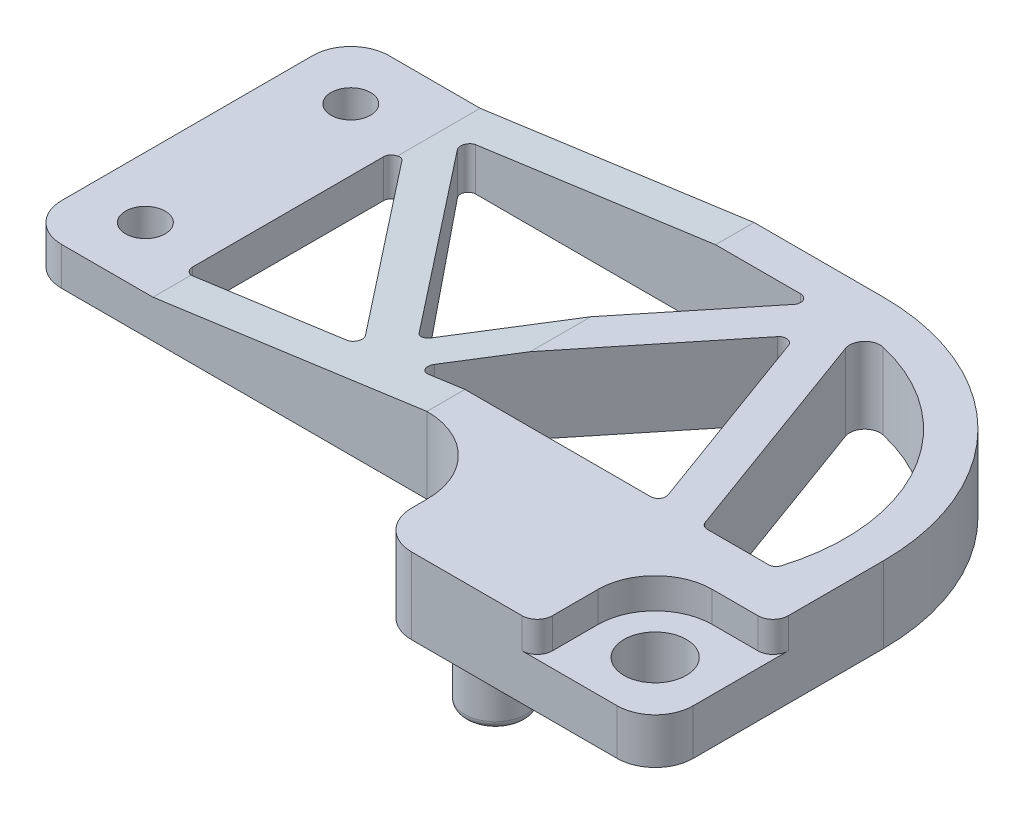
SolidWorks part; units mm, degrees
ref_plane "Front Plane" through (0, 0, 0) normal (0, 0, 1) x (1, 0, 0)
ref_plane "Top Plane" through (0, 0, 0) normal (0, 1, 0) x (1, 0, 0)
ref_plane "Right Plane" through (0, 0, 0) normal (1, 0, 0) x (0, 0, -1)
sketch "Sketch1" plane through (0, 0, 0) normal (0, 1, 0) x (1, 0, 0)
  line L0 (-15.9009, 67.2516) -> (-15.9009, 34.3134) construction
  line L1 (11.2739, 72.3134) -> (4.7921, 72.3134)
  line L2 (41.2739, 42.3134) -> (41.2739, 17.3134)
  line L3 (36.2739, 12.3134) -> (9.2739, 12.3134)
  line L4 (4.2739, 19.3134) -> (4.2739, 17.3134)
  line L5 (4.7921, 72.3134) -> (-53.7261, 72.3134)
  line L7 (-5.7261, 29.3134) -> (-53.7261, 29.3134)
  line L8 (-58.7261, 67.3134) -> (-58.7261, 34.3134)
  line L9 (34.1714, 34.3134) -> (26.1348, 34.3134)
  line L10 (-42.5577, 35.3134) -> (-42.5577, 60.4524)
  line L11 (-37.2458, 67.2516) -> (5.4439, 67.2516)
  line L12 (-42.5577, 67.2516) -> (-15.9009, 34.3134) construction
  line L13 (10.7558, 67.2516) -> (22.7739, 34.3134) construction
  line L14 (-15.9009, 34.3134) -> (10.7558, 67.2516) construction
  line L15 (-40.7803, 61.0815) -> (-20.4355, 35.9425)
  line L16 (-38.0231, 65.6225) -> (-16.6783, 39.2479)
  line L18 (6.2213, 65.6225) -> (-15.1236, 39.2479)
  line L19 (-21.2128, 34.3134) -> (-41.5577, 34.3134)
  line L20 (25.1954, 34.9706) -> (14.6158, 63.9661)
  line L21 (19.6228, 35.6562) -> (10.5265, 60.5866)
  line L22 (8.8097, 60.8729) -> (-11.3664, 35.9425)
  line L23 (18.6834, 34.3134) -> (-10.589, 34.3134)
  circle A0 centre (33.2739, 20.3134) radius 4.1
  circle A1 centre (12.2739, 20.3134) radius 4
  circle A2 centre (-50.7261, 64.3134) radius 2.6
  circle A3 centre (-50.7261, 37.3134) radius 2.6
  arc A4 (4.2739, 19.3134) -> (-5.7261, 29.3134) centre (-5.7261, 19.3134) ccw
  arc A5 (11.2739, 72.3134) -> (41.2739, 42.3134) centre (11.2739, 42.3134) cw
  arc A6 (41.2739, 17.3134) -> (36.2739, 12.3134) centre (36.2739, 17.3134) cw
  arc A7 (9.2739, 12.3134) -> (4.2739, 17.3134) centre (9.2739, 17.3134) cw
  arc A8 (-53.7261, 72.3134) -> (-58.7261, 67.3134) centre (-53.7261, 67.3134) ccw
  arc A9 (-53.7261, 29.3134) -> (-58.7261, 34.3134) centre (-53.7261, 34.3134) cw
  arc A12 (-20.4355, 35.9425) -> (-21.2128, 34.3134) centre (-21.2128, 35.3134) cw
  arc A13 (35.1277, 35.0211) -> (16.9525, 66.602) centre (11.2739, 42.3134) ccw
  arc A14 (-41.5577, 34.3134) -> (-42.5577, 35.3134) centre (-41.5577, 35.3134) cw
  arc A15 (-40.7803, 61.0815) -> (-42.5577, 60.4524) centre (-41.5577, 60.4524) ccw
  arc A16 (-16.6783, 39.2479) -> (-15.1236, 39.2479) centre (-15.9009, 39.877) ccw
  arc A17 (6.2213, 65.6225) -> (5.4439, 67.2516) centre (5.4439, 66.2516) ccw
  arc A18 (-38.0231, 65.6225) -> (-37.2458, 67.2516) centre (-37.2458, 66.2516) cw
  arc A19 (35.1277, 35.0211) -> (34.1714, 34.3134) centre (34.1714, 35.3134) cw
  arc A20 (25.1954, 34.9706) -> (26.1348, 34.3134) centre (26.1348, 35.3134) ccw
  arc A21 (19.6228, 35.6562) -> (18.6834, 34.3134) centre (18.6834, 35.3134) cw
  arc A22 (10.5265, 60.5866) -> (8.8097, 60.8729) centre (9.587, 60.2438) ccw
  arc A23 (-10.589, 34.3134) -> (-11.3664, 35.9425) centre (-10.589, 35.3134) cw
  arc A24 (16.9525, 66.602) -> (14.6158, 63.9661) centre (16.4967, 64.6524) ccw
  point P47 (-19.1171, 34.3134)
  point P54 (-15.9009, 38.2874)
  point P65 (20.1127, 34.3134)
  point P68 (9.921, 62.246)
  dimension "D1" = 21
  dimension "D9" = 27
  dimension "D13" = 10
  dimension "D14" = 30
  dimension "D15" = 5
  dimension "D16" = 2.5
  dimension "D21" = 1
  dimension "D22" = 1
  dimension "D23" = 1
  dimension "D19" = 8.2
  dimension "D24" = 8
  dimension "D25" = 5.2
  dimension "D26" = 5.2
  dimension "D2" = 8
  dimension "D3" = 8
  dimension "D4" = 8
  dimension "D5" = 8
  dimension "D6" = 60
  dimension "D7" = 100
  dimension "D8" = 43
  dimension "D10" = 8
  dimension "D11" = 8
  dimension "D12" = 8
  dimension "D17" = 2.5
  dimension "D18" = 2.5
  dimension "D20" = 2.5
extrude "Boss-Extrude1" add sketch "Sketch1" along normal blind 10
sketch "Sketch2" plane through (0, 10, 0) normal (0, 1, 0) x (1, 0, 0)
  line L0 (33.2739, 27.8134) -> (41.2739, 27.8134)
  line L1 (41.2739, 17.3134) -> (41.2739, 42.3134) construction
  line L2 (41.2739, 27.8134) -> (41.2739, 17.3134)
  line L3 (25.7739, 20.3134) -> (25.7739, 12.3134)
  line L4 (9.2739, 12.3134) -> (36.2739, 12.3134) construction
  line L5 (25.7739, 12.3134) -> (36.2739, 12.3134)
  arc A0 (33.2739, 27.8134) -> (25.7739, 20.3134) centre (33.2739, 20.3134) ccw
  arc A1 (36.2739, 12.3134) -> (41.2739, 17.3134) centre (36.2739, 17.3134) ccw
extrude "Cut-Extrude1" cut sketch "Sketch2" against normal blind 4
fillet "Fillet1" radius 2 2 edges at (41.2739, 8, -27.8134) (25.7739, 8, -12.3134)
sketch "Sketch3" plane through (0, 10, 0) normal (0, 1, 0) x (1, 0, 0)
  circle A0 centre (12.2739, 20.3134) radius 4
  circle A1 centre (12.2739, 20.3134) radius 4 construction
extrude "Boss-Extrude2" add sketch "Sketch3" against normal blind 20
fillet "Fillet2" radius 1 2 edges at (12.2739, -10, -16.3134) (12.2739, 0, -16.3134)
sketch "Sketch4" plane through (0, 0, -29.3134) normal (0, 0, 1) x (1, 0, 0)
  line L0 (-5.7261, 10) -> (-41.7261, 5)
  line L1 (-41.7261, 5) -> (-62.3663, 5)
  line L2 (-5.7261, 10) -> (-62.3663, 10)
  line L3 (-62.3663, 10) -> (-62.3663, 5)
  line L4 (-53.7261, 0) -> (-5.7261, 0) construction
  line L5 (-53.7261, 10) -> (-53.7261, 0) construction
  point P8 (0, 0)
  point P11 (0, 0)
  dimension "D1" = 5
  dimension "D2" = 12
extrude "Cut-Extrude2" cut sketch "Sketch4" against normal up to surface (43 mm away) up to face at (-21.2261, 5, -72.3134)
